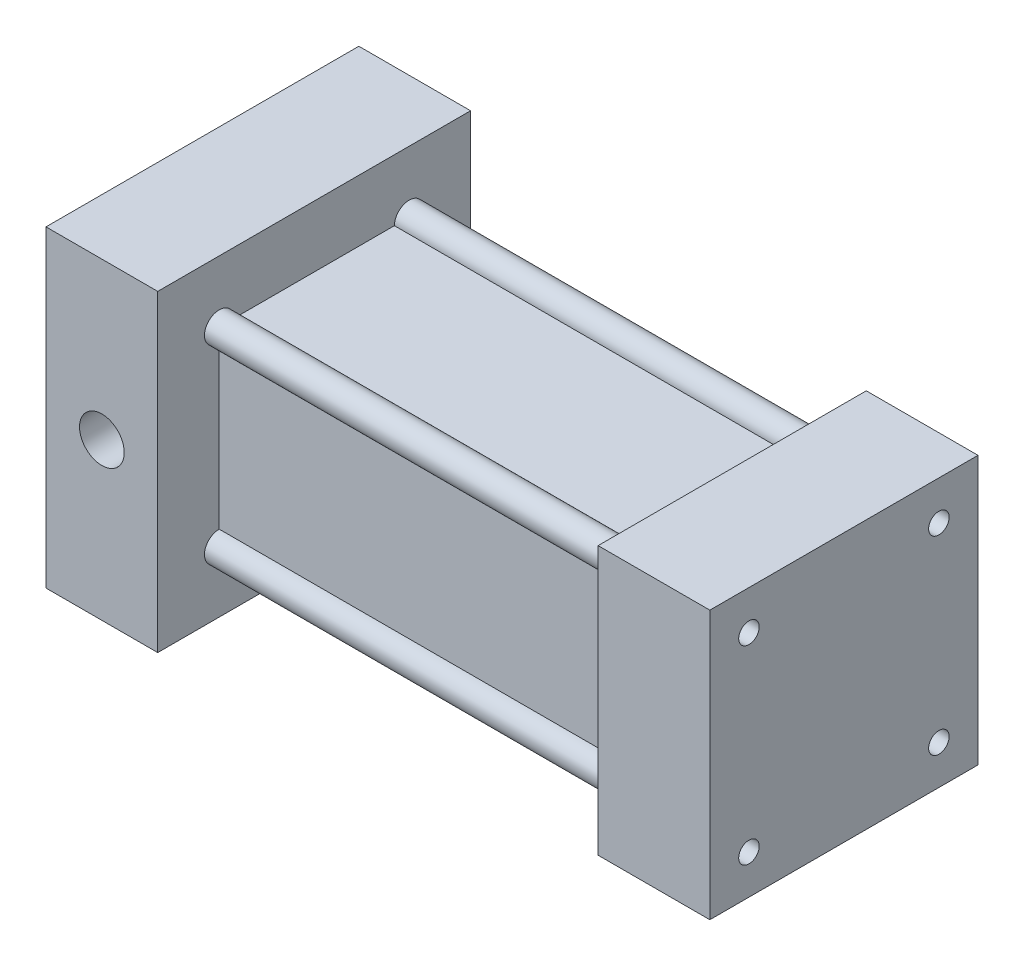
SolidWorks part; units mm, degrees
ref_plane "Plane1" through (0, 0, 0) normal (0, 0, 1) x (1, 0, 0)
ref_plane "Plane2" through (0, 0, 0) normal (0, 1, 0) x (1, 0, 0)
ref_plane "Plane3" through (0, 0, 0) normal (1, 0, 0) x (0, 0, -1)
other "Configuration Table"
sketch "Sketch1" plane through (0, 0, 0) normal (0, 0, 1) x (1, 0, 0)
  line L0 (-7.9375, -22.225) -> (7.9375, -22.225)
  line L1 (-7.9375, -22.225) -> (-7.9375, 22.225)
  line L2 (7.9375, 22.225) -> (-7.9375, 22.225)
  line L3 (7.9375, 22.225) -> (7.9375, -22.225)
  point P4 (7.9375, 0)
  point P5 (0, -22.225)
  dimension "D1" = 44.45
  dimension "D2" = 15.875
extrude "Base-Extrude" add sketch "Sketch1" along normal mid plane 44.45
sketch "Sketch2" plane through (7.9375, 0, 0) normal (1, 0, 0) x (0, 0, -1)
  line L0 (-13.4925, 13.4925) -> (13.4925, 13.4925)
  line L1 (-13.4925, 13.4925) -> (-13.4925, -13.4925)
  line L2 (13.4925, -13.4925) -> (-13.4925, -13.4925)
  line L3 (13.4925, -13.4925) -> (13.4925, 13.4925)
  point P4 (0, -13.4925)
  point P5 (13.4925, 0)
  dimension "D1" = 26.985
extrude "Boss-Extrude1" add sketch "Sketch2" along normal blind 59.3954
sketch "Sketch3" plane through (67.3329, -2.9165, 3.3691) normal (1, 0, 0) x (0, 0, -1)
  line L0 (-15.6809, 21.9665) -> (22.4191, 21.9665)
  line L1 (-15.6809, 21.9665) -> (-15.6809, -16.1335)
  line L2 (22.4191, -16.1335) -> (-15.6809, -16.1335)
  line L3 (22.4191, -16.1335) -> (22.4191, 21.9665)
  point P4 (3.3691, -16.1335)
  point P5 (22.4191, 2.9165)
  dimension "D1" = 38.1
extrude "Boss-Extrude2" add sketch "Sketch3" along normal blind 15.875
sketch "Sketch4" plane through (7.9375, 0, 0) normal (1, 0, 0) x (0, 0, -1)
  line L0 (-13.4925, 13.4925) -> (13.4925, 13.4925) construction
  circle A0 centre (-13.4925, 13.4925) radius 2.093
  circle A1 centre (-13.4925, -13.4925) radius 2.093
  circle A2 centre (13.4925, 13.4925) radius 2.093
  circle A3 centre (13.4925, -13.4925) radius 2.093
  dimension "D1" = 4.1859
extrude "Boss-Extrude3" add sketch "Sketch4" along normal up to surface (59.3954 mm away) up to face at (67.3329, 0, 0)
sketch "Sketch5" plane through (83.2079, 0, 0) normal (1, 0, 0) x (0, 0, -1)
  circle A0 centre (-13.4925, 13.4925) radius 1.458
  arc A2 (-11.3995, 13.4925) -> (-13.4925, 11.3995) centre (-13.4925, 13.4925) ccw construction
  circle A3 centre (-13.4925, -13.4925) radius 1.458
  circle A4 centre (13.4925, 13.4925) radius 1.458
  circle A5 centre (13.4925, -13.4925) radius 1.458
  arc A6 (-13.4925, -11.3995) -> (-11.3995, -13.4925) centre (-13.4925, -13.4925) ccw construction
  arc A7 (13.4925, 11.3995) -> (11.3995, 13.4925) centre (13.4925, 13.4925) ccw construction
  arc A8 (11.3995, -13.4925) -> (13.4925, -11.3995) centre (13.4925, -13.4925) ccw construction
  dimension "D1" = 2.9159
extrude "Cut-Extrude1" cut sketch "Sketch5" against normal up to surface (75.2704 mm away) up to face at (7.9375, 0, 0)
sketch "Sketch6" plane through (-7.9375, 0, 0) normal (-1, 0, 0) x (0, 0, 1)
  circle A0 centre (0, 0) radius 4.7625
  dimension "D1" = 9.525
extrude "Cut-Extrude2" cut sketch "Sketch6" against normal up to surface (75.2704 mm away) up to face at (67.3329, 0, 0)
sketch "Sketch8" plane through (0, 0, 22.225) normal (0, 0, 1) x (1, 0, 0)
  circle A0 centre (0, 0) radius 3.175
  dimension "D1" = 6.35
extrude "Cut-Extrude3" cut sketch "Sketch8" against normal blind 6.35
mirror "Mirror1" about plane through (0, 0, 0) normal (0, 0, 1) of "Cut-Extrude3"
